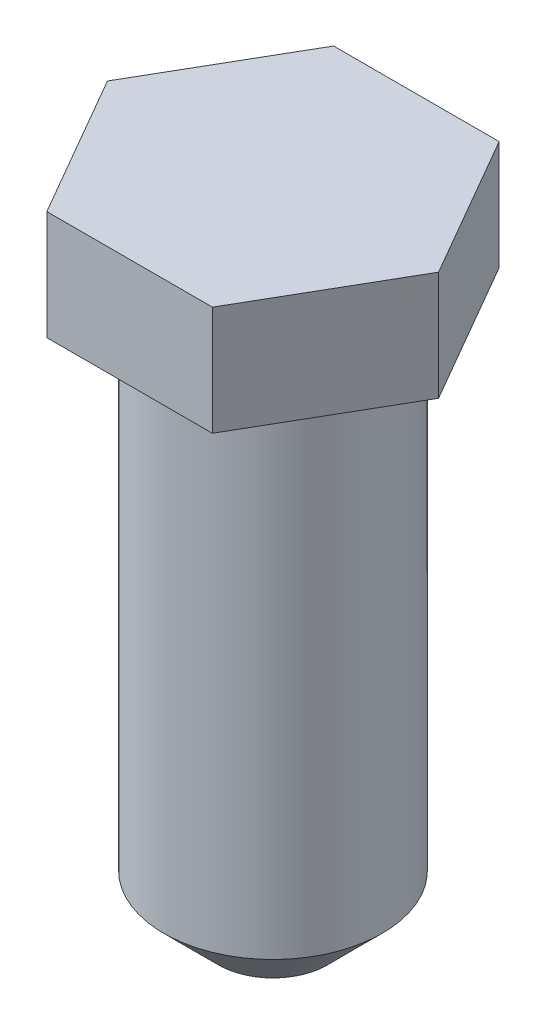
SolidWorks part; units mm, degrees
ref_plane "Front Plane" through (0, 0, 0) normal (0, 0, 1) x (1, 0, 0)
ref_plane "Top Plane" through (0, 0, 0) normal (0, 1, 0) x (1, 0, 0)
ref_plane "Right Plane" through (0, 0, 0) normal (1, 0, 0) x (0, 0, -1)
sketch "Sketch5" plane through (0, 0, 0) normal (0, 1, 0) x (1, 0, 0)
  line L1 (19.2474, 0) -> (9.6237, 16.6688)
  line L2 (9.6237, 16.6688) -> (-9.6237, 16.6687)
  line L3 (-9.6237, 16.6687) -> (-19.2474, 0)
  line L4 (-19.2474, 0) -> (-9.6237, -16.6688)
  line L5 (-9.6237, -16.6688) -> (9.6237, -16.6687)
  line L6 (9.6237, -16.6687) -> (19.2474, 0)
  circle A0 centre (0, 0) radius 16.6688 construction
  dimension "D1" = 33.3375
  dimension "D2" = 16.6687
extrude "Boss-Extrude2" add sketch "Sketch5" along normal blind 12.7
sketch "Sketch6" plane through (0, 0, 0) normal (0, -1, 0) x (1, 0, 0)
  circle A0 centre (0, 0) radius 12.7
  dimension "D1" = 25.4
extrude "Boss-Extrude3" add sketch "Sketch6" along normal blind 57.15
sketch "Sketch7" plane through (0, 0, 16.6688) normal (0, 0, 1) x (1, 0, 0)
  line L0 (-12.7, 0) -> (-12.7, -57.15) construction
  line L1 (12.7, 0) -> (-12.7, 0)
  line L2 (12.7, 0) -> (12.7, -31.75)
  line L3 (12.7, -31.75) -> (-12.7, -31.75)
  line L4 (-12.7, 0) -> (-12.7, -31.75)
  dimension "D1" = 31.75
sketch "Sketch10" plane through (0, -57.15, 0) normal (0, -1, 0) x (1, 0, 0)
  circle A0 centre (0, 0) radius 12.7
extrude "Boss-Extrude5" add sketch "Sketch10" along normal blind 6.35
chamfer "Chamfer2" distance 6.35 angle 45 1 edges at (0, -63.5, -12.7)
